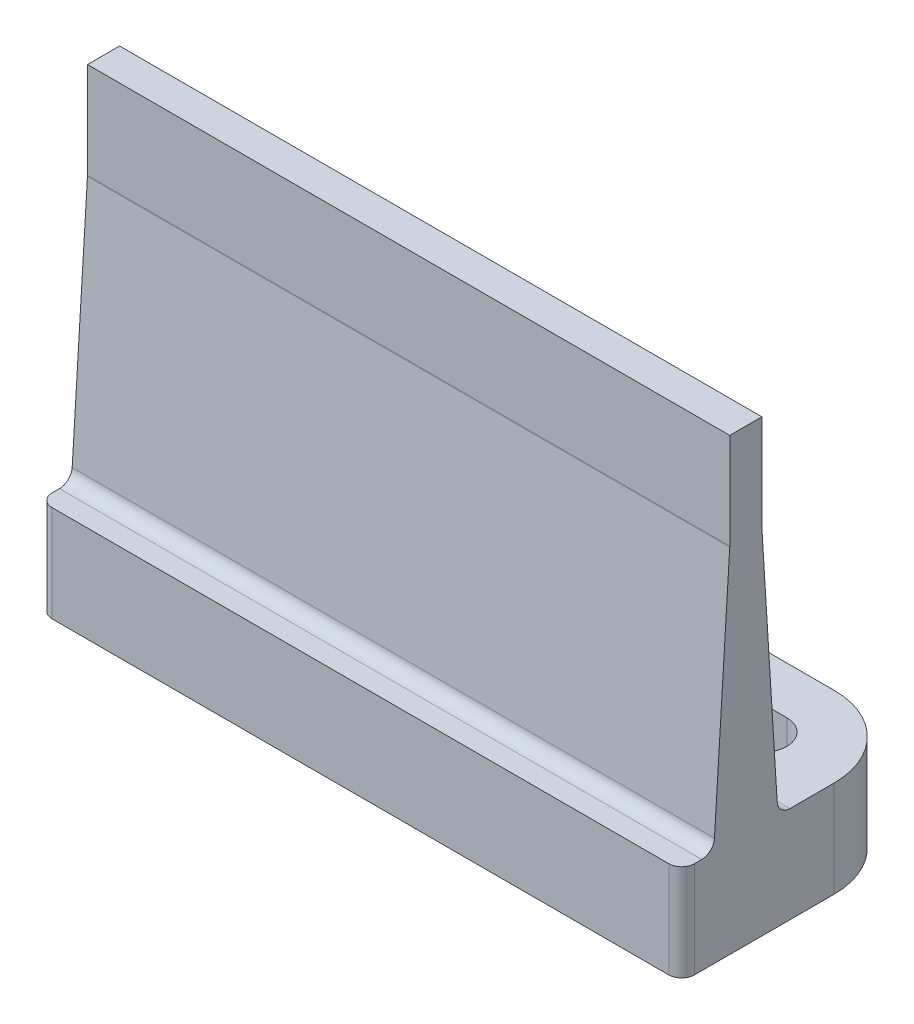
SolidWorks part; units mm, degrees
material "ABS"
ref_plane "Front Plane" through (0, 0, 0) normal (0, 0, 1) x (1, 0, 0)
ref_plane "Top Plane" through (0, 0, 0) normal (0, 1, 0) x (1, 0, 0)
ref_plane "Right Plane" through (0, 0, 0) normal (1, 0, 0) x (0, 0, -1)
sketch "Sketch1" plane through (0, 0, 0) normal (1, 0, 0) x (0, 0, -1)
  line L0 (-4, 0) -> (10.5, 0)
  line L1 (10.5, 0) -> (10.5, 6)
  line L2 (10.5, 6) -> (2, 6)
  line L4 (1, 28) -> (-1, 28)
  line L6 (-2, 6) -> (-4, 6)
  line L7 (-4, 6) -> (-4, 0)
  line L8 (0, 15.4) -> (0, -15.4) construction
  line L9 (2, 6) -> (1, 22)
  line L10 (1, 22) -> (1, 28)
  line L11 (-1, 28) -> (-1, 22)
  line L13 (-1, 22) -> (-2, 6)
  point P8 (0, 28)
  dimension "D1" = 10.5
  dimension "D2" = 6
  dimension "D3" = 4
  dimension "D4" = 28
  dimension "D5" = 2
  dimension "D6" = 6
  dimension "D7" = 4
extrude "Boss-Extrude1" add sketch "Sketch1" along normal mid plane 40
sketch "Sketch4" plane through (0, 6, 0) normal (0, 1, 0) x (1, 0, 0)
  line L0 (-15, 6) -> (-5, 6) construction
  line L1 (-15, 7.55) -> (-5, 7.55)
  line L2 (-15, 4.45) -> (-5, 4.45)
  line L3 (5, 6) -> (15, 6) construction
  line L4 (5, 7.55) -> (15, 7.55)
  line L5 (5, 4.45) -> (15, 4.45)
  line L6 (5, 6) -> (-5, 6) construction
  line L7 (0, -7.975) -> (0, 7.975) construction
  arc A0 (-15, 7.55) -> (-15, 4.45) centre (-15, 6) ccw
  arc A1 (-5, 4.45) -> (-5, 7.55) centre (-5, 6) ccw
  arc A2 (5, 7.55) -> (5, 4.45) centre (5, 6) ccw
  arc A3 (15, 4.45) -> (15, 7.55) centre (15, 6) ccw
  point P2 (-10, 6)
  point P7 (10, 6)
  point P15 (0, 6)
  dimension "D1" = 3.1
  dimension "D2" = 6
  dimension "D3" = 10
  dimension "D4" = 20
extrude "Cut-Extrude1" cut sketch "Sketch4" against normal up to next
fillet "Fillet1" radius 5 2 edges at (20, 3, -10.5) (-20, 3, -10.5)
fillet "Fillet2" radius 0.7937 6 edges at (20, 3, 4) (-20, 3, 4) (0, 6, -2) (0, 22, -1) (0, 22, 1) (0, 6, 2)
